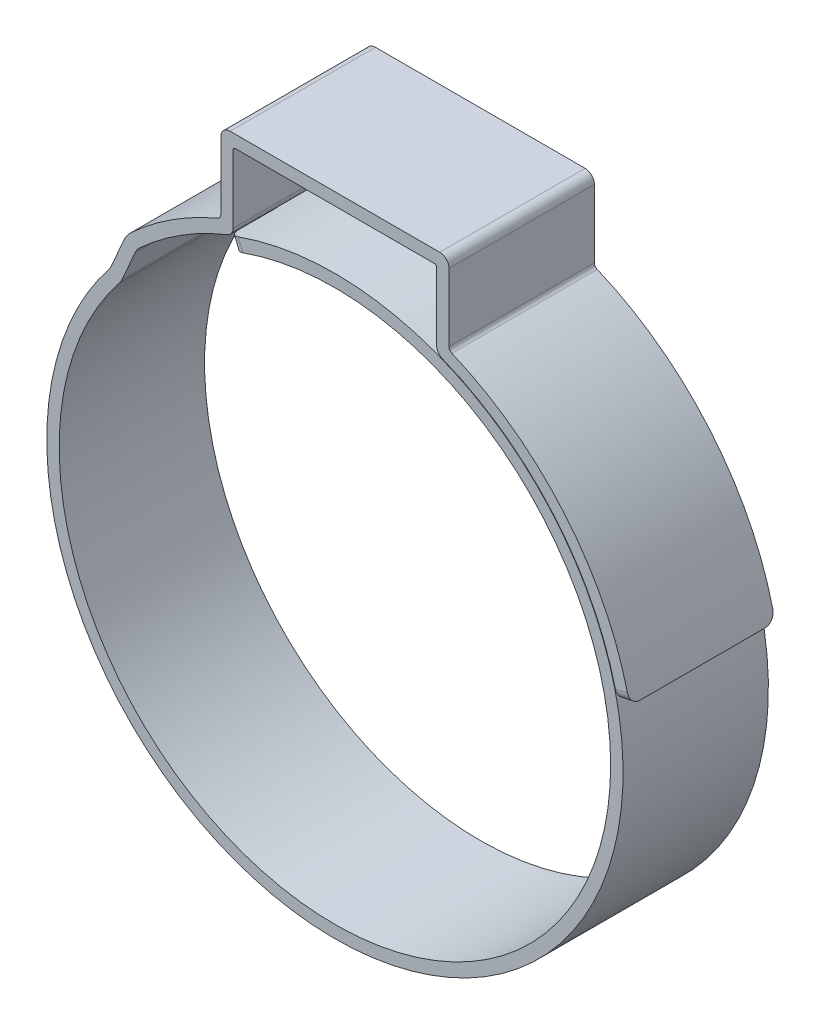
SolidWorks part; units mm, degrees
material "Alloy Steel"
ref_plane "Front" through (0, 0, 0) normal (0, 0, 1) x (1, 0, 0)
ref_plane "Top" through (0, 0, 0) normal (0, 1, 0) x (1, 0, 0)
ref_plane "Right" through (0, 0, 0) normal (1, 0, 0) x (0, 0, -1)
sketch "Sketch1" plane through (0, 0, 0) normal (0, 0, 1) x (1, 0, 0)
  line L0 (0, 0) -> (0, 13.55) construction
  line L1 (0, 13.55) -> (0, 17.0246) construction
  line L2 (-5, 13.55) -> (5, 13.55) construction
  line L3 (-5, 13.2746) -> (-5, 17.0246) construction
  line L4 (-5, 17.0246) -> (5, 17.0246) construction
  line L5 (5, 17.0246) -> (5, 13.2746) construction
  line L6 (-13.55, 0) -> (0, 0) construction
  line L7 (0, 0) -> (13.55, 0) construction
  line L8 (-5.6096, 13.2746) -> (-5.6096, 17.6342)
  line L9 (-5, 13.2746) -> (-5.6096, 13.2746)
  line L10 (-5.6096, 17.6342) -> (5.6096, 17.6342)
  line L11 (5.6096, 17.6342) -> (5.6096, 13.2746)
  line L12 (5.6096, 13.2746) -> (5, 13.2746)
  line L13 (0, 17.0246) -> (0, 17.6342) construction
  line L14 (-5, 13.2746) -> (5, 13.2746)
  circle A0 centre (0, 0) radius 13.55 construction
  circle A1 centre (0, 0) radius 14.1596 construction
  circle A2 centre (0, 0) radius 14.185 construction
  dimension "D3" = 3.75
  dimension "D1" = 0.6096
extrude "Boss-Extrude1" add sketch "Sketch1" along normal mid plane 7.1437
sketch "Sketch4" plane through (0, 17.6342, 0) normal (0, 1, 0) x (1, 0, 0)
  line L0 (-1.9284, 0) -> (-3, 0) construction
  line L1 (0, -1.0716) -> (0, 1.0716) construction
  line L2 (-1.9284, 0) -> (1.9284, 0) construction
  line L3 (-13.55, 0) -> (13.55, 0) construction
  line L4 (-1.9284, 1.0716) -> (1.9284, 1.0716)
  line L5 (-1.9284, -1.0716) -> (1.9284, -1.0716)
  line L6 (1.9284, 0) -> (3, 0) construction
  arc A0 (-1.9284, 1.0716) -> (-1.9284, -1.0716) centre (-1.9284, 0) ccw
  arc A1 (1.9284, -1.0716) -> (1.9284, 1.0716) centre (1.9284, 0) ccw
  point P5 (0, 0)
  dimension "D2" = 2.1431
  dimension "D1" = 6
extrude "Cut-Extrude1" [suppressed] cut sketch "Sketch4" against normal blind 0.75
fillet "Fillet1" [suppressed] radius 0.4875
fillet "Fillet2" [suppressed] radius 0.1875
shell "Shell1" thickness 0.6096
sketch "Sketch5" plane through (0, 0, 0) normal (0, 0, 1) x (1, 0, 0)
  line L0 (13.8927, 2.8646) -> (0, 0) construction
  line L1 (5, 13.2746) -> (0, 0) construction
  arc A0 (5, 13.2746) -> (13.8927, 2.8646) centre (0, 0) cw
  dimension "Connector Strap Length" = 14.2875
extrude "Extrude-Thin3" add sketch "Sketch5" along normal mid plane 7.1437 thin thin type one direction reverse wall 0.6096
sketch "Sketch6" plane through (0, 0, 0) normal (0, 0, 1) x (1, 0, 0)
  line L0 (-9.738, 10.3144) -> (0, 0) construction
  line L2 (-9.8167, 10.1344) -> (-10.4576, 8.6705)
  line L3 (-12.3644, 5.5429) -> (0, 0) construction
  line L4 (-10.5085, 8.5542) -> (0, 0) construction
  arc A0 (-5, 13.2746) -> (-9.589, 10.453) centre (0, 0) ccw
  arc A1 (-12.3644, 5.5429) -> (-5, 12.5937) centre (0, 0) ccw
  arc A2 (-10.4576, 8.6705) -> (-10.5855, 8.4587) centre (-11.3265, 9.0508) cw
  arc A3 (-9.589, 10.453) -> (-9.8167, 10.1344) centre (-8.9479, 9.754) ccw
  arc A4 (-12.3644, 5.5429) -> (-10.5855, 8.4587) centre (0, 0) cw
  circle A5 centre (0, 0) radius 13.55 construction
  dimension "D4" = 0.9485
  dimension "D2" = 15
  dimension "D3" = 7.5
  dimension "D1" = 5.42
extrude "Extrude-Thin4" add sketch "Sketch6" along normal mid plane 7.1437 thin
sketch "Sketch7" plane through (0, 0, 0) normal (0, 0, 1) x (1, 0, 0)
  line L1 (-10.0011, 10.9022) -> (-9.589, 10.453)
  line L3 (-9.589, 10.453) -> (0, 0)
  line L4 (-14.1465, 0.6098) -> (-16.608, 0.7159)
  line L5 (-10.0011, 10.9022) -> (-11.2374, 12.2498)
  line L6 (0, 0) -> (-14.1465, 0.6098)
  arc A0 (-16.608, 0.7159) -> (-11.2374, 12.2498) centre (0, 0) cw
  arc A1 (-9.589, 10.453) -> (-9.8167, 10.1344) centre (-8.9479, 9.754) ccw construction
  arc A2 (-5, 13.2746) -> (-9.589, 10.453) centre (0, 0) ccw construction
  arc A10 (-11.0617, 8.8393) -> (-5.2249, 13.1603) centre (0, 0) ccw construction
  dimension "D1" = 1.8288
  dimension "D2" = 45
extrude "Cut-Extrude2" [suppressed] cut sketch "Sketch7" against normal mid plane 2.432
sketch "Sketch8" [suppressed] plane through (0, 0, 0) normal (0, 0, 1) x (1, 0, 0)
  line L0 (-15.0698, 7.017) -> (0, 0) construction
  line L1 (0, 0) -> (-13.5374, 0.5835) construction
  line L2 (0, 0) -> (-9.589, 10.453) construction
  line L3 (-12.8363, 5.977) -> (-12.2836, 5.7197) construction
  line L4 (-11.3657, 8.2972) -> (0, 0) construction
  line L5 (-13.263, 3.2161) -> (0, 0) construction
  arc A0 (-5, 13.2746) -> (-9.589, 10.453) centre (0, 0) ccw construction
  arc A1 (-5, 13.2746) -> (-9.589, 10.453) centre (0, 0) ccw construction
  arc A2 (-11.2374, 12.2498) -> (-16.608, 0.7159) centre (0, 0) ccw construction
  arc A3 (-13.5374, 0.5835) -> (-5, 12.5937) centre (0, 0) ccw construction
  circle A4 centre (0, 0) radius 14.1596 construction
  arc A5 (-10.5855, 8.4587) -> (-5, 12.5937) centre (0, 0) ccw construction
  circle A6 centre (0, 0) radius 13.55 construction
  arc A7 (-13.5374, 0.5835) -> (-13.263, 3.2161) centre (8.2293, -0.3547) cw
  arc A8 (-13.263, 3.2161) -> (-11.3657, 8.2972) centre (0.7038, 0.8956) cw
  arc A9 (-11.3657, 8.2972) -> (-9.589, 10.453) centre (-2.7833, 3.034) cw
  point P19 (-12.56, 5.8483)
  dimension "D1" = 22.5
extrude "Extrude-Thin5" [suppressed] add sketch "Sketch8" along normal mid plane 2.3813 thin
sketch "Sketch12" [suppressed] plane through (0, 0, 0) normal (0, 0, 1) x (1, 0, 0)
  line L0 (-5.6453, -0.2315) -> (0, 0) construction
  line L1 (0, 0) -> (-4.5478, 4.1895) construction
  line L2 (-5.5488, 2.0363) -> (0, 0) construction
  arc A0 (-2.75, 5.5382) -> (-4.5478, 4.1895) centre (0, 0) ccw construction
  arc A1 (-2.75, 5.5382) -> (-4.5478, 4.1895) centre (0, 0) ccw construction
  arc A2 (-5.6453, -0.2315) -> (0, -5.65) centre (0, 0) ccw construction
  arc A3 (-5.6453, -0.2315) -> (-5.5488, 2.0363) centre (7.9561, 0.3262) cw
  arc A4 (-5.5488, 2.0363) -> (-4.5478, 4.1895) centre (-1.6784, 1.5462) cw
  dimension "D1" = 22.5
extrude "Extrude-Thin7" [suppressed] add sketch "Sketch12" along normal mid plane 2.3813 thin
sketch "Sketch9" plane through (0, 0, 0) normal (0, 0, 1) x (1, 0, 0)
  line L0 (0, 0) -> (-9.1598, 9.985) construction
  line L4 (-10.0011, 10.9022) -> (-9.1598, 9.985) construction
  arc A0 (-5, 12.5937) -> (-9.1598, 9.985) centre (0, 0) ccw
  circle A1 centre (0, 0) radius 13.55 construction
extrude "Extrude-Thin6" add sketch "Sketch9" along normal mid plane 2.3813 thin
sketch "Sketch10" plane through (0, 0, 0) normal (0, 0, 1) x (1, 0, 0)
  line L0 (0, 0) -> (13.7663, 5.4193) construction
  line L1 (0, 0) -> (13.251, 6.5796) construction
  line L2 (0, 0) -> (12.6381, 7.6915) construction
  line L3 (0, 0) -> (11.9321, 8.7467) construction
  line L4 (0, 0) -> (14.4898, 2.9877) construction
  line L5 (0, 0) -> (11.1383, 9.7375) construction
  line L6 (0, 0) -> (10.2624, 10.6566) construction
  line L7 (10.2624, 10.6566) -> (9.8219, 10.1992)
  line L8 (11.1383, 9.7375) -> (10.6602, 9.3196)
  line L9 (11.9321, 8.7467) -> (11.42, 8.3713)
  line L10 (12.6381, 7.6915) -> (12.0957, 7.3613)
  line L11 (13.251, 6.5796) -> (12.6823, 6.2972)
  line L12 (13.7663, 5.4193) -> (13.1755, 5.1867)
  arc A0 (14.4898, 2.9877) -> (5.6096, 13.6899) centre (0, 0) ccw construction
  arc A1 (10.2624, 10.6566) -> (11.1383, 9.7375) centre (0, 0) cw
  circle A2 centre (0, 0) radius 14.1596 construction
  arc A3 (9.8219, 10.1992) -> (10.6602, 9.3196) centre (0, 0) cw
  arc A4 (11.9321, 8.7467) -> (12.6381, 7.6915) centre (0, 0) cw
  arc A5 (13.251, 6.5796) -> (13.7663, 5.4193) centre (0, 0) cw
  arc A6 (11.42, 8.3713) -> (12.0957, 7.3613) centre (0, 0) cw
  arc A7 (12.6823, 6.2972) -> (13.1755, 5.1867) centre (0, 0) cw
  dimension "D3" = 1.27
  dimension "D4" = 1.27
  dimension "D5" = 1.27
  dimension "D6" = 1.27
extrude "Cut-Extrude3" [suppressed] cut sketch "Sketch10" against normal mid plane 1.7859
fillet "Fillet4" radius 0.4572 4 edges at (5.6096, 17.6342, 0) (-5.6096, 17.6342, 0) (5, 13.2746, 0) (-5, 13.2746, 0)
fillet "Fillet5" radius 0.2286 2 edges at (5.6096, 13.6899, 0) (-5.6096, 13.6899, 0)
fillet "Fillet6" radius 0.1143 2 edges at (5, 17.0246, 0) (-5, 17.0246, 0)
fillet "Fillet7" radius 0.508 6 edges at (14.1913, 2.9262, -3.5719) (14.1913, 2.9262, 3.5719) (-5.1125, 12.877, -3.5719) (-5.1125, 12.877, 3.5719) (-9.3658, 10.2096, 1.1906) (-9.3658, 10.2096, -1.1906)
sketch "Sketch11" [suppressed] plane through (0, 0, 0) normal (0, 0, 1) x (1, 0, 0)
  line L0 (13.251, 6.5796) -> (12.6823, 6.2972) construction
  line L2 (13.251, 6.5796) -> (12.705, 6.3085) construction
  line L3 (13.7663, 5.4193) -> (13.1755, 5.1867) construction
  line L4 (13.1991, 5.196) -> (13.7663, 5.4193) construction
  line L5 (12.6935, 6.2744) -> (13.8584, 6.0578)
  line L6 (12.6935, 6.2744) -> (13.2623, 6.5568) construction
  line L8 (14.2769, 4.9924) -> (13.9932, 4.8807)
  line L9 (13.9932, 4.8807) -> (0, 0) construction
  line L10 (11.435, 8.3508) -> (12.2333, 8.3203)
  line L11 (12.8075, 7.7648) -> (12.1088, 7.3396)
  line L12 (11.2927, 9.8387) -> (10.632, 10.2879)
  line L13 (11.2927, 9.8387) -> (10.6769, 9.3004)
  line L14 (10.6793, 9.3363) -> (11.1383, 9.7375) construction
  line L15 (12.1174, 7.3745) -> (12.6381, 7.6915) construction
  line L16 (9.8402, 10.1816) -> (10.2807, 10.639) construction
  line L17 (10.2624, 10.6566) -> (9.8396, 10.2175) construction
  line L18 (11.435, 8.3508) -> (11.9471, 8.7262) construction
  line L19 (11.9321, 8.7467) -> (11.4405, 8.3863) construction
  line L20 (10.632, 10.2879) -> (9.8402, 10.1816)
  line L21 (12.2333, 8.3203) -> (12.8075, 7.7648)
  line L22 (13.7806, 5.4522) -> (13.1661, 5.2103) construction
  line L23 (13.7806, 5.4522) -> (13.0068, 5.5961)
  arc A0 (13.7806, 5.4522) -> (13.9932, 4.8807) centre (0, 0) cw
  arc A1 (-11.0617, 8.8393) -> (-4.7494, 13.3393) centre (0, 0) ccw construction
  arc A2 (13.8584, 6.0578) -> (14.2769, 4.9924) centre (0, 0) cw
  arc A3 (12.6935, 6.2744) -> (13.0068, 5.5961) centre (0, 0) cw
  arc A5 (14.3786, 3.4835) -> (5.7494, 13.6318) centre (0, 0) ccw construction
  arc A6 (11.435, 8.3508) -> (12.1088, 7.3396) centre (0, 0) cw
  arc A7 (9.8402, 10.1816) -> (10.6769, 9.3004) centre (0, 0) cw
  point P24 (11.155, 9.7184)
  point P41 (12.6513, 7.6697)
  dimension "D2" = 0.0254
  dimension "D5" = 0.6096
  dimension "D7" = 0.0254
  dimension "D8" = 0.0254
  dimension "D9" = 0.0254
  dimension "D10" = 0.0254
  dimension "D11" = 0.1829
  dimension "D12" = 0.1829
  dimension "D3" = 0.0254
  dimension "D6" = 0.6096
  dimension "D13" = 0.3048
extrude "Boss-Extrude2" [suppressed] add sketch "Sketch11" along normal mid plane 1.6589
sketch "Ref" plane through (0, 0, 0) normal (0, 0, 1) x (1, 0, 0)
  line L1 (5.1524, 17.6342) -> (-5.1524, 17.6342) construction
  line L2 (5.6096, 17.6342) -> (-5.6096, 17.6342)
  line L4 (4.8857, 17.0246) -> (-4.8857, 17.0246) construction
  line L7 (5.6096, 17.0246) -> (-5.6096, 17.0246)
  line L8 (-5.6096, 17.177) -> (-5.6096, 13.8424) construction
  line L9 (5.6096, 13.8424) -> (5.6096, 17.177) construction
equation "\"D3@Sketch1\" = \"Ear Width (Inside)@Sketch1\" * .375"
equation "\"D2@Sketch4\" = \"Band Wd@Boss-Extrude1\" * .3"
equation "\"D1@Sketch4\" = \"Ear Width (Inside)@Sketch1\" * .6"
equation "\"D1@Cut-Extrude1\" = \"D3@Sketch1\" * .2"
equation "\"D1@Shell1\" = \"Band Thickness@Sketch1\""
equation "\"D5@Extrude-Thin3\" = \"Band Thickness@Sketch1\""
equation "\"D1@Extrude-Thin3\" = \"Band Wd@Boss-Extrude1\""
equation "\"D5@Extrude-Thin4\" = \"Band Thickness@Sketch1\""
equation "\"D1@Extrude-Thin4\" = \"Band Wd@Boss-Extrude1\""
equation "\"D1@Fillet4\" = \"Band Thickness@Sketch1\" * .75"
equation "\"D1@Fillet5\" = \"D1@Fillet4\" * .5"
equation "\"D1@Fillet6\" = \"D1@Fillet4\" * .25"
equation "\"D1@Fillet1\" = \"D1@Cut-Extrude1\" * .65"
equation "\"D1@Fillet2\" = \"D1@Cut-Extrude1\" * .25"
equation "\"D1@Sketch1\" = \"Band Thickness@Sketch1\""
equation "\"D1@Cut-Extrude2\" = ( \"Band Wd@Boss-Extrude1\" / 3 ) + .002"
equation "\"D1@Extrude-Thin5\" = \"Band Wd@Boss-Extrude1\" / 3"
equation "\"D5@Extrude-Thin5\" = \"Band Thickness@Sketch1\""
equation "\"D1@Extrude-Thin6\" = \"D1@Extrude-Thin5\""
equation "\"D5@Extrude-Thin6\" = \"Band Thickness@Sketch1\""
equation "\"D1@Cut-Extrude3\" = \"Band Wd@Boss-Extrude1\" * .25"
equation "\"D11@Sketch11\" = \"Band Thickness@Sketch1\" * .3"
equation "\"D12@Sketch11\" = \"D11@Sketch11\""
equation "\"D1@Boss-Extrude2\" = \"D1@Cut-Extrude3\" - .005"
equation "\"D4@Sketch6\" = \"Clamp ID@Sketch1\" * .035"
equation "\"D1@Sketch7\" = \"Band Thickness@Sketch1\" * 3"
equation "\"D3@Sketch10\" = \"D2@Sketch10\""
equation "\"D4@Sketch10\" = \"D3@Sketch10\""
equation "\"D5@Sketch10\" = \"D2@Sketch10\""
equation "\"D6@Sketch10\" = \"D2@Sketch10\""
equation "\"D5@Sketch11\" = \"Band Thickness@Sketch1\""
equation "\"D6@Sketch11\" = \"Band Thickness@Sketch1\""
equation "\"D13@Sketch11\" = \"Band Thickness@Sketch1\" / 2"
equation "\"D1@Sketch6\" = \"Clamp ID@Sketch1\" * .2"
equation "\"D1@Extrude-Thin7\" = \"Band Wd@Boss-Extrude1\" / 3"
equation "\"D5@Extrude-Thin7\" = \"Band Thickness@Sketch1\""
